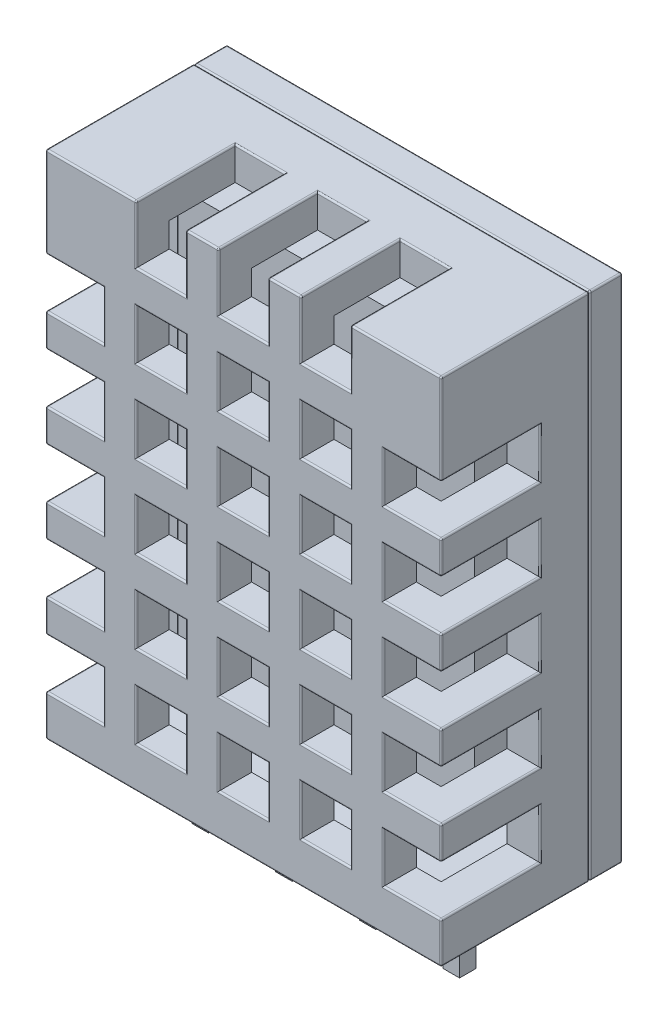
SolidWorks part; units mm, degrees
ref_plane "Front Plane" through (0, 0, 0) normal (0, 0, 1) x (1, 0, 0)
ref_plane "Top Plane" through (0, 0, 0) normal (0, 1, 0) x (1, 0, 0)
ref_plane "Right Plane" through (0, 0, 0) normal (1, 0, 0) x (0, 0, -1)
sketch "Sketch1" plane through (0, 0, 0) normal (0, 0, 1) x (1, 0, 0)
  line L1 (0, 0) -> (12, 0)
  line L2 (0, 0) -> (0, 15.5)
  line L3 (0, 15.5) -> (12, 15.5)
  line L4 (12, 0) -> (12, 15.5)
  dimension "D1" = 12
  dimension "D2" = 15.5
extrude "Boss-Extrude1" add sketch "Sketch1" along normal blind 5.5
sketch "Sketch2" plane through (0, 0, 0) normal (0, -1, 0) x (1, 0, 0)
  line L0 (0, 5.5) -> (0, 0) construction
  line L1 (1.94, 3) -> (2.44, 3)
  line L2 (1.94, 3) -> (1.94, 2.5)
  line L3 (1.94, 2.5) -> (2.44, 2.5)
  line L4 (2.44, 3) -> (2.44, 2.5)
  line L5 (0, 2.75) -> (12, 2.75) construction
  line L6 (12, 5.5) -> (12, 0) construction
  line L7 (4.48, 3) -> (4.98, 3)
  line L8 (4.48, 3) -> (4.48, 2.5)
  line L9 (4.48, 2.5) -> (4.98, 2.5)
  line L10 (4.98, 3) -> (4.98, 2.5)
  line L11 (7.02, 3) -> (7.52, 3)
  line L12 (7.02, 3) -> (7.02, 2.5)
  line L13 (7.02, 2.5) -> (7.52, 2.5)
  line L14 (7.52, 3) -> (7.52, 2.5)
  line L15 (9.56, 3) -> (10.06, 3)
  line L16 (9.56, 3) -> (9.56, 2.5)
  line L17 (9.56, 2.5) -> (10.06, 2.5)
  line L18 (10.06, 3) -> (10.06, 2.5)
  point P11 (1.94, 2.75)
  dimension "D1" = 0.5
  dimension "D2" = 0.5
  dimension "D3" = 1.94
  dimension "D4" = 4
extrude "Boss-Extrude2" add sketch "Sketch2" along normal blind 2.5
shell "Shell2" thickness 1
sketch "Sketch3" plane through (0, 0, 5.5) normal (0, 0, 1) x (1, 0, 0)
  line L0 (12, 15.5) -> (0, 15.5) construction
  line L1 (2.75, 15.5) -> (4.25, 15.5)
  line L2 (2.75, 15.5) -> (2.75, 13.75)
  line L3 (2.75, 13.75) -> (4.25, 13.75)
  line L4 (4.25, 15.5) -> (4.25, 13.75)
  line L5 (5.25, 15.5) -> (6.75, 15.5)
  line L6 (5.25, 15.5) -> (5.25, 13.75)
  line L7 (5.25, 13.75) -> (6.75, 13.75)
  line L8 (6.75, 15.5) -> (6.75, 13.75)
  line L9 (7.75, 15.5) -> (9.25, 15.5)
  line L10 (7.75, 15.5) -> (7.75, 13.75)
  line L11 (7.75, 13.75) -> (9.25, 13.75)
  line L12 (9.25, 15.5) -> (9.25, 13.75)
  line L13 (0, 15.5) -> (0, 0) construction
  dimension "D1" = 1.5
  dimension "D2" = 1.75
  dimension "D4" = 2.75
  dimension "D3" = 3
extrude "Cut-Extrude1" cut sketch "Sketch3" against normal blind 3
sketch "Sketch4" plane through (0, 0, 5.5) normal (0, 0, 1) x (1, 0, 0)
  line L0 (2.75, 13.75) -> (4.25, 13.75) construction
  line L1 (2.75, 12.75) -> (4.25, 12.75)
  line L2 (2.75, 12.75) -> (2.75, 11.25)
  line L3 (2.75, 11.25) -> (4.25, 11.25)
  line L4 (4.25, 12.75) -> (4.25, 11.25)
  line L5 (0, 15.5) -> (0, 0) construction
  line L6 (5.25, 12.75) -> (6.75, 12.75)
  line L7 (5.25, 12.75) -> (5.25, 11.25)
  line L8 (5.25, 11.25) -> (6.75, 11.25)
  line L9 (6.75, 12.75) -> (6.75, 11.25)
  line L10 (7.75, 12.75) -> (9.25, 12.75)
  line L11 (7.75, 12.75) -> (7.75, 11.25)
  line L12 (7.75, 11.25) -> (9.25, 11.25)
  line L13 (9.25, 12.75) -> (9.25, 11.25)
  line L14 (5.25, 10.25) -> (6.75, 10.25)
  line L15 (5.25, 10.25) -> (5.25, 8.75)
  line L16 (5.25, 8.75) -> (6.75, 8.75)
  line L17 (6.75, 10.25) -> (6.75, 8.75)
  line L18 (7.75, 10.25) -> (9.25, 10.25)
  line L19 (7.75, 10.25) -> (7.75, 8.75)
  line L20 (7.75, 8.75) -> (9.25, 8.75)
  line L21 (9.25, 10.25) -> (9.25, 8.75)
  line L22 (5.25, 7.75) -> (6.75, 7.75)
  line L23 (5.25, 7.75) -> (5.25, 6.25)
  line L24 (5.25, 6.25) -> (6.75, 6.25)
  line L25 (6.75, 7.75) -> (6.75, 6.25)
  line L26 (7.75, 7.75) -> (9.25, 7.75)
  line L27 (7.75, 7.75) -> (7.75, 6.25)
  line L28 (7.75, 6.25) -> (9.25, 6.25)
  line L29 (9.25, 7.75) -> (9.25, 6.25)
  line L30 (5.25, 5.25) -> (6.75, 5.25)
  line L31 (5.25, 5.25) -> (5.25, 3.75)
  line L32 (5.25, 3.75) -> (6.75, 3.75)
  line L33 (6.75, 5.25) -> (6.75, 3.75)
  line L34 (7.75, 5.25) -> (9.25, 5.25)
  line L35 (7.75, 5.25) -> (7.75, 3.75)
  line L36 (7.75, 3.75) -> (9.25, 3.75)
  line L37 (9.25, 5.25) -> (9.25, 3.75)
  line L38 (5.25, 2.75) -> (6.75, 2.75)
  line L39 (5.25, 2.75) -> (5.25, 1.25)
  line L40 (5.25, 1.25) -> (6.75, 1.25)
  line L41 (6.75, 2.75) -> (6.75, 1.25)
  line L42 (7.75, 2.75) -> (9.25, 2.75)
  line L43 (7.75, 2.75) -> (7.75, 1.25)
  line L44 (7.75, 1.25) -> (9.25, 1.25)
  line L45 (9.25, 2.75) -> (9.25, 1.25)
  line L46 (2.75, 10.25) -> (4.25, 10.25)
  line L47 (2.75, 10.25) -> (2.75, 8.75)
  line L48 (2.75, 8.75) -> (4.25, 8.75)
  line L49 (4.25, 10.25) -> (4.25, 8.75)
  line L50 (2.75, 7.75) -> (4.25, 7.75)
  line L51 (2.75, 7.75) -> (2.75, 6.25)
  line L52 (2.75, 6.25) -> (4.25, 6.25)
  line L53 (4.25, 7.75) -> (4.25, 6.25)
  line L54 (2.75, 5.25) -> (4.25, 5.25)
  line L55 (2.75, 5.25) -> (2.75, 3.75)
  line L56 (2.75, 3.75) -> (4.25, 3.75)
  line L57 (4.25, 5.25) -> (4.25, 3.75)
  line L58 (2.75, 2.75) -> (4.25, 2.75)
  line L59 (2.75, 2.75) -> (2.75, 1.25)
  line L60 (2.75, 1.25) -> (4.25, 1.25)
  line L61 (4.25, 2.75) -> (4.25, 1.25)
  dimension "D1" = 1.5
  dimension "D2" = 1
  dimension "D3" = 2.75
  dimension "D4" = 3
  dimension "D5" = 5
extrude "Cut-Extrude2" cut sketch "Sketch4" against normal blind 3
sketch "Sketch5" plane through (0, 0, 5.5) normal (0, 0, 1) x (1, 0, 0)
  line L0 (0, 15.5) -> (0, 0) construction
  line L1 (0, 12.75) -> (1.75, 12.75)
  line L2 (0, 12.75) -> (0, 11.25)
  line L3 (0, 11.25) -> (1.75, 11.25)
  line L4 (1.75, 12.75) -> (1.75, 11.25)
  line L7 (2.75, 12.75) -> (2.75, 11.25) construction
  line L8 (10.25, 12.75) -> (12, 12.75)
  line L9 (10.25, 12.75) -> (10.25, 11.25)
  line L10 (10.25, 11.25) -> (12, 11.25)
  line L11 (12, 12.75) -> (12, 11.25)
  line L12 (10.25, 10.25) -> (12, 10.25)
  line L13 (10.25, 10.25) -> (10.25, 8.75)
  line L14 (10.25, 8.75) -> (12, 8.75)
  line L15 (12, 10.25) -> (12, 8.75)
  line L16 (10.25, 7.75) -> (12, 7.75)
  line L17 (10.25, 7.75) -> (10.25, 6.25)
  line L18 (10.25, 6.25) -> (12, 6.25)
  line L19 (12, 7.75) -> (12, 6.25)
  line L20 (10.25, 5.25) -> (12, 5.25)
  line L21 (10.25, 5.25) -> (10.25, 3.75)
  line L22 (10.25, 3.75) -> (12, 3.75)
  line L23 (12, 5.25) -> (12, 3.75)
  line L24 (10.25, 2.75) -> (12, 2.75)
  line L25 (10.25, 2.75) -> (10.25, 1.25)
  line L26 (10.25, 1.25) -> (12, 1.25)
  line L27 (12, 2.75) -> (12, 1.25)
  line L28 (0, 10.25) -> (1.75, 10.25)
  line L29 (0, 10.25) -> (0, 8.75)
  line L30 (0, 8.75) -> (1.75, 8.75)
  line L31 (1.75, 10.25) -> (1.75, 8.75)
  line L32 (0, 7.75) -> (1.75, 7.75)
  line L33 (0, 7.75) -> (0, 6.25)
  line L34 (0, 6.25) -> (1.75, 6.25)
  line L35 (1.75, 7.75) -> (1.75, 6.25)
  line L36 (0, 5.25) -> (1.75, 5.25)
  line L37 (0, 5.25) -> (0, 3.75)
  line L38 (0, 3.75) -> (1.75, 3.75)
  line L39 (1.75, 5.25) -> (1.75, 3.75)
  line L40 (0, 2.75) -> (1.75, 2.75)
  line L41 (0, 2.75) -> (0, 1.25)
  line L42 (0, 1.25) -> (1.75, 1.25)
  line L43 (1.75, 2.75) -> (1.75, 1.25)
  dimension "D1" = 1
  dimension "D2" = 2
  dimension "D3" = 5
extrude "Cut-Extrude3" cut sketch "Sketch5" against normal blind 3
sketch "Sketch6" plane through (0, 0, 0) normal (0, 0, -1) x (-1, 0, 0)
  line L4 (0, 0) -> (0, 15.5)
  line L5 (0, 15.5) -> (-12, 15.5)
  line L6 (-12, 15.5) -> (-12, 0)
  line L7 (-12, 0) -> (0, 0)
  line L8 (0, 0) -> (0, 15.5)
  line L9 (0, 15.5) -> (-12, 15.5)
  line L10 (-12, 15.5) -> (-12, 0)
  line L11 (-12, 0) -> (0, 0)
  line L12 (-1, 14.5) -> (-11, 14.5)
  line L13 (-1, 1) -> (-1, 14.5)
  line L14 (-11, 1) -> (-1, 1)
  line L15 (-11, 14.5) -> (-11, 1)
  line L16 (-1, 14.5) -> (-11, 14.5)
  line L17 (-1, 1) -> (-1, 14.5)
  line L18 (-11, 1) -> (-1, 1)
  line L19 (-11, 14.5) -> (-11, 1)
  dimension "D1" = 0
  dimension "D2" = 0
extrude "Cut-Extrude4" cut sketch "Sketch6" against normal blind 1
ref_plane "Plane1" through (0, 0, 0.99) normal (0, 0, 1) x (1, 0, 0)
sketch "Sketch8" plane through (0, 0, 0.99) normal (0, 0, 1) x (1, 0, 0)
  line L4 (0, 0) -> (12, 0)
  line L5 (0, 15.5) -> (0, 0)
  line L6 (12, 15.5) -> (0, 15.5)
  line L7 (12, 0) -> (12, 15.5)
  line L8 (0, 0) -> (12, 0)
  line L9 (0, 15.5) -> (0, 0)
  line L10 (12, 15.5) -> (0, 15.5)
  line L11 (12, 0) -> (12, 15.5)
  dimension "D1" = 0
extrude "Boss-Extrude3" add sketch "Sketch8" against normal blind 0.99 separate body
sketch "Sketch9" plane through (0, 0, 0) normal (0, -1, 0) x (1, 0, 0)
  line L0 (1.94, 3) -> (1.94, 2.5) construction
  line L1 (1.94, 2.5) -> (2.44, 2.5) construction
  line L2 (2.44, 2.5) -> (2.44, 3) construction
  line L3 (2.44, 3) -> (1.94, 3) construction
  line L4 (4.48, 3) -> (4.48, 2.5) construction
  line L5 (4.48, 2.5) -> (4.98, 2.5) construction
  line L6 (4.98, 2.5) -> (4.98, 3) construction
  line L7 (4.98, 3) -> (4.48, 3) construction
  line L8 (7.02, 3) -> (7.02, 2.5) construction
  line L9 (7.02, 2.5) -> (7.52, 2.5) construction
  line L10 (7.52, 2.5) -> (7.52, 3) construction
  line L11 (7.52, 3) -> (7.02, 3) construction
  line L12 (9.56, 3) -> (9.56, 2.5) construction
  line L13 (9.56, 2.5) -> (10.06, 2.5) construction
  line L14 (10.06, 2.5) -> (10.06, 3) construction
  line L15 (10.06, 3) -> (9.56, 3) construction
  line L16 (1.94, 3) -> (1.94, 2.5)
  line L17 (1.94, 2.5) -> (2.44, 2.5)
  line L18 (2.44, 2.5) -> (2.44, 3)
  line L19 (2.44, 3) -> (1.94, 3)
  line L20 (4.48, 3) -> (4.48, 2.5)
  line L21 (4.48, 2.5) -> (4.98, 2.5)
  line L22 (4.98, 2.5) -> (4.98, 3)
  line L23 (4.98, 3) -> (4.48, 3)
  line L24 (7.02, 3) -> (7.02, 2.5)
  line L25 (7.02, 2.5) -> (7.52, 2.5)
  line L26 (7.52, 2.5) -> (7.52, 3)
  line L27 (7.52, 3) -> (7.02, 3)
  line L28 (9.56, 3) -> (9.56, 2.5)
  line L29 (9.56, 2.5) -> (10.06, 2.5)
  line L30 (10.06, 2.5) -> (10.06, 3)
  line L31 (10.06, 3) -> (9.56, 3)
  line L32 (1.84, 3.1) -> (1.84, 2.4)
  line L33 (1.84, 2.4) -> (2.54, 2.4)
  line L34 (2.54, 2.4) -> (2.54, 3.1)
  line L35 (2.54, 3.1) -> (1.84, 3.1)
  line L36 (4.38, 3.1) -> (4.38, 2.4)
  line L37 (4.38, 2.4) -> (5.08, 2.4)
  line L38 (5.08, 2.4) -> (5.08, 3.1)
  line L39 (5.08, 3.1) -> (4.38, 3.1)
  line L40 (6.92, 3.1) -> (6.92, 2.4)
  line L41 (6.92, 2.4) -> (7.62, 2.4)
  line L42 (7.62, 2.4) -> (7.62, 3.1)
  line L43 (7.62, 3.1) -> (6.92, 3.1)
  line L44 (9.46, 3.1) -> (9.46, 2.4)
  line L45 (9.46, 2.4) -> (10.16, 2.4)
  line L46 (10.16, 2.4) -> (10.16, 3.1)
  line L47 (10.16, 3.1) -> (9.46, 3.1)
  dimension "D1" = 0.1
extrude "Cut-Extrude5" cut sketch "Sketch9" against normal blind 1
fillet "Fillet1" radius 0.05 104 edges at (6, 0, 1) (1.84, 0, 2.75) (4.73, 0, 2.4) (5.08, 0, 2.75) (4.73, 0, 3.1) (9.81, 0, 2.4) (10.16, 0, 2.75) (9.46, 0, 2.75) (0, 12, 2.5) (0, 10.25, 4) (0, 8.75, 4) (0, 7, 2.5) (0, 5.25, 4) (0, 4.5, 2.5) (0, 3.75, 4) (0, 2.75, 4) (0, 2, 2.5) (0, 1.25, 4) (9.25, 15.5, 4) (7.75, 15.5, 4) (6, 15.5, 2.5) (5.25, 15.5, 4) (4.25, 15.5, 4) (2.75, 15.5, 4) (6, 15.5, 1) (12, 1.25, 4) (12, 2.75, 4) (12, 3.75, 4) (12, 4.5, 2.5) (12, 5.25, 4) (12, 6.25, 4) (12, 7.75, 4) (12, 8.75, 4) (12, 10.25, 4) (12, 12.75, 4) (12, 15.5, 3.25) (0.875, 3.75, 5.5) (1.75, 7, 5.5) (0, 8.25, 5.5) (1.75, 9.5, 5.5) (0, 10.75, 5.5) (1.75, 12, 5.5) (0, 14.125, 5.5) (1.375, 15.5, 5.5) (2.75, 14.625, 5.5) (3.5, 13.75, 5.5) (5.25, 14.625, 5.5) (9.25, 14.625, 5.5) (12, 14.125, 5.5) (11.125, 12.75, 5.5) (10.25, 12, 5.5) (12, 10.75, 5.5) (10.25, 9.5, 5.5) (12, 8.25, 5.5) (11.125, 7.75, 5.5) (10.25, 7, 5.5) (11.125, 6.25, 5.5) (12, 5.75, 5.5) (11.125, 5.25, 5.5) (11.125, 3.75, 5.5) (12, 3.25, 5.5) (11.125, 2.75, 5.5) (10.25, 2, 5.5) (11.125, 1.25, 5.5) (12, 0.625, 5.5) (6, 0, 5.5) (1.75, 2, 5.5) (0, 3.25, 5.5) (3.5, 11.25, 5.5) (6, 11.25, 5.5) (9.25, 12, 5.5) (8.5, 12.75, 5.5) (7.75, 12, 5.5) (8.5, 11.25, 5.5) (5.25, 9.5, 5.5) (6, 8.75, 5.5) (9.25, 9.5, 5.5) (8.5, 10.25, 5.5) (7.75, 9.5, 5.5) (8.5, 8.75, 5.5) (5.25, 7, 5.5) (9.25, 7, 5.5) (8.5, 7.75, 5.5) (8.5, 6.25, 5.5) (5.25, 4.5, 5.5) (9.25, 4.5, 5.5) (8.5, 5.25, 5.5) (8.5, 3.75, 5.5) (6.75, 2, 5.5) (6, 2.75, 5.5) (5.25, 2, 5.5) (6, 1.25, 5.5) (9.25, 2, 5.5) (8.5, 2.75, 5.5) (7.75, 2, 5.5) (4.25, 9.5, 5.5) (2.75, 9.5, 5.5) (3.5, 8.75, 5.5) (4.25, 7, 5.5) (3.5, 7.75, 5.5) (2.75, 7, 5.5) (3.5, 6.25, 5.5) (4.25, 4.5, 5.5) (3.5, 3.75, 5.5)
fillet "Fillet2" radius 0.05 12 edges at (6, 15.5, 0.99) (0, 15.5, 0.495) (0, 7.75, 0.99) (0, 0, 0.495) (6, 0, 0.99) (12, 15.5, 0.495) (12, 0, 0.495) (12, 7.75, 0.99) (6, 15.5, 0) (0, 7.75, 0) (6, 0, 0) (12, 7.75, 0)
sketch "Sketch10" plane through (0, 0, 0.99) normal (0, 0, 1) x (1, 0, 0)
  line L14 (1.5, 1.5) -> (10.5, 1.5)
  line L15 (10.5, 1.5) -> (10.5, 14)
  line L16 (10.5, 14) -> (1.5, 14)
  line L17 (1.5, 14) -> (1.5, 1.5)
  line L18 (1.5, 1.5) -> (10.5, 1.5)
  line L19 (10.5, 1.5) -> (10.5, 14)
  line L20 (10.5, 14) -> (1.5, 14)
  line L21 (1.5, 14) -> (1.5, 1.5)
  dimension "D1" = 0.5
extrude "Boss-Extrude4" add sketch "Sketch10" along normal blind 2
